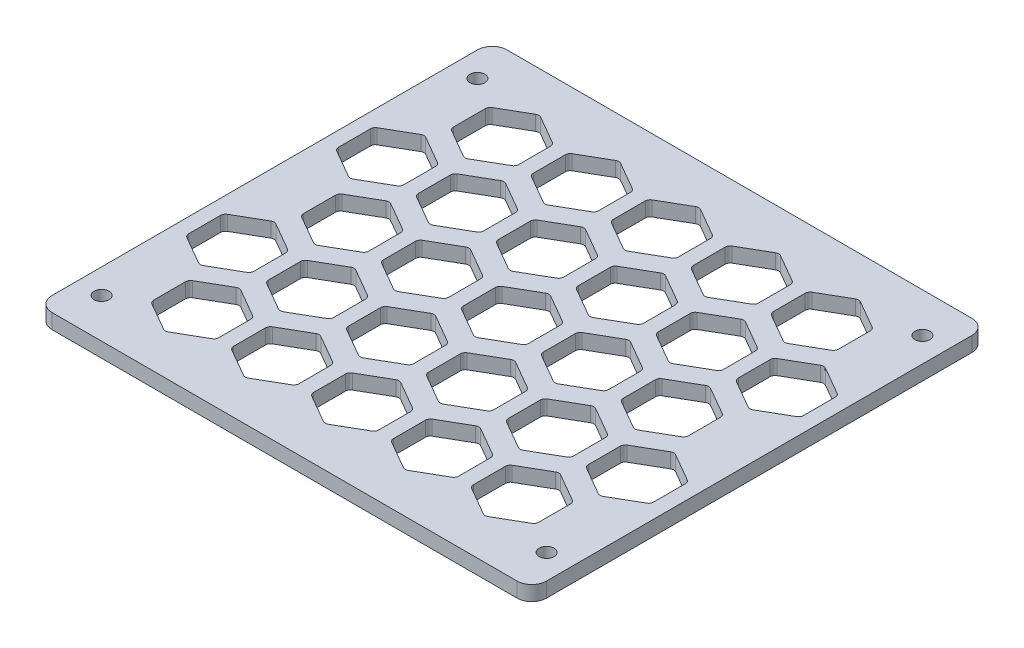
SolidWorks part; units mm, degrees
ref_plane "前视基准面" through (0, 0, 0) normal (0, 0, 1) x (1, 0, 0)
ref_plane "上视基准面" through (0, 0, 0) normal (0, 1, 0) x (1, 0, 0)
ref_plane "右视基准面" through (0, 0, 0) normal (1, 0, 0) x (0, 0, -1)
other "Configuration Table"
sketch "草图1" plane through (0, 0, 0) normal (0, 1, 0) x (1, 0, 0)
  line L1 (-50, 46) -> (50, 46)
  line L2 (-50, 46) -> (-50, -46)
  line L3 (-50, -46) -> (50, -46)
  line L4 (50, 46) -> (50, -46)
  line L5 (-50, 46) -> (50, -46) construction
  line L6 (-50, -46) -> (50, 46) construction
  line L7 (-45, -38) -> (45, -38) construction
  line L8 (-45, -38) -> (-45, 38) construction
  line L9 (-45, 38) -> (45, 38) construction
  line L10 (45, -38) -> (45, 38) construction
  line L11 (-45, -38) -> (45, 38) construction
  line L12 (-45, 38) -> (45, -38) construction
  circle A1 centre (-45, 38) radius 1.5
  circle A2 centre (45, 38) radius 1.5
  circle A3 centre (45, -38) radius 1.5
  circle A4 centre (-45, -38) radius 1.5
  point P0 (0, 0)
  point P6 (0, 0)
  dimension "D5" = 3
  dimension "D1" = 100
  dimension "D2" = 92
  dimension "D3" = 5
  dimension "D4" = 8
extrude "凸台-拉伸1" add sketch "草图1" along normal blind 3
fillet "圆角1" radius 3 4 edges at (-50, 1.5, 46) (-50, 1.5, -46) (50, 1.5, -46) (50, 1.5, 46)
sketch "草图2" plane through (0, 3, 0) normal (0, 1, 0) x (1, 0, 0)
  line L0 (0, 0) -> (0, 46) construction
  line L1 (-32.3333, 22.7091) -> (-25.75, 26.51)
  line L2 (-25.75, 26.51) -> (-25.75, 34.1118)
  line L3 (-25.75, 34.1118) -> (-32.3333, 37.9127)
  line L4 (-32.3333, 37.9127) -> (-38.9167, 34.1118)
  line L5 (-38.9167, 34.1118) -> (-38.9167, 26.51)
  line L6 (-38.9167, 26.51) -> (-32.3333, 22.7091)
  line L13 (-16.1667, 37.9127) -> (-22.75, 34.1118)
  line L14 (-22.75, 34.1118) -> (-22.75, 26.51)
  line L15 (-22.75, 26.51) -> (-16.1667, 22.7091)
  line L16 (-16.1667, 22.7091) -> (-9.5833, 26.51)
  line L17 (-9.5833, 26.51) -> (-9.5833, 34.1118)
  line L18 (-9.5833, 34.1118) -> (-16.1667, 37.9127)
  line L19 (47, 46) -> (-47, 46) construction
  line L20 (-32.3333, 30.3109) -> (0, 30.3109) construction
  line L21 (0, 37.9127) -> (-6.5833, 34.1118)
  line L22 (-6.5833, 34.1118) -> (-6.5833, 26.51)
  line L23 (-6.5833, 26.51) -> (0, 22.7091)
  line L24 (0, 22.7091) -> (6.5833, 26.51)
  line L25 (6.5833, 26.51) -> (6.5833, 34.1118)
  line L26 (6.5833, 34.1118) -> (0, 37.9127)
  line L27 (-40.4167, 15.1554) -> (-8.0833, 15.1554) construction
  line L28 (-40.4167, 22.7572) -> (-47, 18.9563)
  line L29 (-47, 18.9563) -> (-47, 11.3546)
  line L30 (-47, 11.3546) -> (-40.4167, 7.5537)
  line L31 (-40.4167, 7.5537) -> (-33.8333, 11.3546)
  line L32 (-33.8333, 11.3546) -> (-33.8333, 18.9563)
  line L33 (-33.8333, 18.9563) -> (-40.4167, 22.7572)
  line L34 (-24.25, 22.7572) -> (-30.8333, 18.9563)
  line L35 (-30.8333, 18.9563) -> (-30.8333, 11.3546)
  line L36 (-30.8333, 11.3546) -> (-24.25, 7.5537)
  line L37 (-24.25, 7.5537) -> (-17.6667, 11.3546)
  line L38 (-17.6667, 11.3546) -> (-17.6667, 18.9563)
  line L39 (-17.6667, 18.9563) -> (-24.25, 22.7572)
  line L40 (-8.0833, 22.7572) -> (-14.6667, 18.9563)
  line L41 (-14.6667, 18.9563) -> (-14.6667, 11.3546)
  line L42 (-14.6667, 11.3546) -> (-8.0833, 7.5537)
  line L43 (-8.0833, 7.5537) -> (-1.5, 11.3546)
  line L44 (-1.5, 11.3546) -> (-1.5, 18.9563)
  line L45 (-1.5, 18.9563) -> (-8.0833, 22.7572)
  line L46 (-32.3333, 0) -> (0, 0) construction
  line L47 (6.5833, -3.8009) -> (0, -7.6018)
  line L48 (6.5833, 3.8009) -> (6.5833, -3.8009)
  line L49 (0, 7.6018) -> (6.5833, 3.8009)
  line L50 (-6.5833, 3.8009) -> (0, 7.6018)
  line L51 (-6.5833, -3.8009) -> (-6.5833, 3.8009)
  line L52 (0, -7.6018) -> (-6.5833, -3.8009)
  line L53 (-9.5833, -3.8009) -> (-16.1667, -7.6018)
  line L54 (-9.5833, 3.8009) -> (-9.5833, -3.8009)
  line L55 (-16.1667, 7.6018) -> (-9.5833, 3.8009)
  line L56 (-22.75, 3.8009) -> (-16.1667, 7.6018)
  line L57 (-22.75, -3.8009) -> (-22.75, 3.8009)
  line L58 (-16.1667, -7.6018) -> (-22.75, -3.8009)
  line L59 (-38.9167, 3.8009) -> (-32.3333, 7.6018)
  line L60 (-38.9167, -3.8009) -> (-38.9167, 3.8009)
  line L61 (-32.3333, -7.6018) -> (-38.9167, -3.8009)
  line L62 (-25.75, -3.8009) -> (-32.3333, -7.6018)
  line L63 (-25.75, 3.8009) -> (-25.75, -3.8009)
  line L64 (-32.3333, 7.6018) -> (-25.75, 3.8009)
  line L66 (-50, 43) -> (-50, -43) construction
  line L67 (9.5833, 3.8009) -> (9.5833, -3.8009)
  line L68 (16.1667, 7.6018) -> (9.5833, 3.8009)
  line L69 (22.75, 3.8009) -> (16.1667, 7.6018)
  line L70 (22.75, -3.8009) -> (22.75, 3.8009)
  line L71 (16.1667, -7.6018) -> (22.75, -3.8009)
  line L72 (9.5833, -3.8009) -> (16.1667, -7.6018)
  line L73 (38.9167, -3.8009) -> (38.9167, 3.8009)
  line L74 (32.3333, -7.6018) -> (38.9167, -3.8009)
  line L75 (25.75, -3.8009) -> (32.3333, -7.6018)
  line L76 (25.75, 3.8009) -> (25.75, -3.8009)
  line L77 (32.3333, 7.6018) -> (25.75, 3.8009)
  line L78 (38.9167, 3.8009) -> (32.3333, 7.6018)
  line L79 (33.8333, 18.9563) -> (40.4167, 22.7572)
  line L80 (33.8333, 11.3546) -> (33.8333, 18.9563)
  line L81 (40.4167, 7.5537) -> (33.8333, 11.3546)
  line L82 (47, 11.3546) -> (40.4167, 7.5537)
  line L83 (47, 18.9563) -> (47, 11.3546)
  line L84 (40.4167, 22.7572) -> (47, 18.9563)
  line L85 (1.5, 18.9563) -> (8.0833, 22.7572)
  line L86 (1.5, 11.3546) -> (1.5, 18.9563)
  line L87 (8.0833, 7.5537) -> (1.5, 11.3546)
  line L88 (14.6667, 11.3546) -> (8.0833, 7.5537)
  line L89 (14.6667, 18.9563) -> (14.6667, 11.3546)
  line L90 (8.0833, 22.7572) -> (14.6667, 18.9563)
  line L91 (17.6667, 18.9563) -> (24.25, 22.7572)
  line L92 (17.6667, 11.3546) -> (17.6667, 18.9563)
  line L93 (24.25, 7.5537) -> (17.6667, 11.3546)
  line L94 (30.8333, 11.3546) -> (24.25, 7.5537)
  line L95 (30.8333, 18.9563) -> (30.8333, 11.3546)
  line L96 (24.25, 22.7572) -> (30.8333, 18.9563)
  line L97 (9.5833, 34.1118) -> (16.1667, 37.9127)
  line L98 (9.5833, 26.51) -> (9.5833, 34.1118)
  line L99 (16.1667, 22.7091) -> (9.5833, 26.51)
  line L100 (22.75, 26.51) -> (16.1667, 22.7091)
  line L101 (22.75, 34.1118) -> (22.75, 26.51)
  line L102 (16.1667, 37.9127) -> (22.75, 34.1118)
  line L103 (38.9167, 26.51) -> (32.3333, 22.7091)
  line L104 (38.9167, 34.1118) -> (38.9167, 26.51)
  line L105 (32.3333, 37.9127) -> (38.9167, 34.1118)
  line L106 (25.75, 34.1118) -> (32.3333, 37.9127)
  line L107 (25.75, 26.51) -> (25.75, 34.1118)
  line L108 (32.3333, 22.7091) -> (25.75, 26.51)
  line L109 (-40.4167, -15.1554) -> (-8.0833, -15.1554) construction
  line L110 (-32.3333, -30.3109) -> (0, -30.3109) construction
  line L111 (32.3333, -22.7091) -> (25.75, -26.51)
  line L112 (25.75, -26.51) -> (25.75, -34.1118)
  line L113 (25.75, -34.1118) -> (32.3333, -37.9127)
  line L114 (32.3333, -37.9127) -> (38.9167, -34.1118)
  line L115 (38.9167, -34.1118) -> (38.9167, -26.51)
  line L116 (38.9167, -26.51) -> (32.3333, -22.7091)
  line L117 (16.1667, -37.9127) -> (22.75, -34.1118)
  line L118 (22.75, -34.1118) -> (22.75, -26.51)
  line L119 (22.75, -26.51) -> (16.1667, -22.7091)
  line L120 (16.1667, -22.7091) -> (9.5833, -26.51)
  line L121 (9.5833, -26.51) -> (9.5833, -34.1118)
  line L122 (9.5833, -34.1118) -> (16.1667, -37.9127)
  line L123 (24.25, -22.7572) -> (30.8333, -18.9563)
  line L124 (30.8333, -18.9563) -> (30.8333, -11.3546)
  line L125 (30.8333, -11.3546) -> (24.25, -7.5537)
  line L126 (24.25, -7.5537) -> (17.6667, -11.3546)
  line L127 (17.6667, -11.3546) -> (17.6667, -18.9563)
  line L128 (17.6667, -18.9563) -> (24.25, -22.7572)
  line L129 (8.0833, -22.7572) -> (14.6667, -18.9563)
  line L130 (14.6667, -18.9563) -> (14.6667, -11.3546)
  line L131 (14.6667, -11.3546) -> (8.0833, -7.5537)
  line L132 (8.0833, -7.5537) -> (1.5, -11.3546)
  line L133 (1.5, -11.3546) -> (1.5, -18.9563)
  line L134 (1.5, -18.9563) -> (8.0833, -22.7572)
  line L135 (40.4167, -22.7572) -> (47, -18.9563)
  line L136 (47, -18.9563) -> (47, -11.3546)
  line L137 (47, -11.3546) -> (40.4167, -7.5537)
  line L138 (40.4167, -7.5537) -> (33.8333, -11.3546)
  line L139 (33.8333, -11.3546) -> (33.8333, -18.9563)
  line L140 (33.8333, -18.9563) -> (40.4167, -22.7572)
  line L141 (-1.5, -18.9563) -> (-8.0833, -22.7572)
  line L142 (-1.5, -11.3546) -> (-1.5, -18.9563)
  line L143 (-8.0833, -7.5537) -> (-1.5, -11.3546)
  line L144 (-14.6667, -11.3546) -> (-8.0833, -7.5537)
  line L145 (-14.6667, -18.9563) -> (-14.6667, -11.3546)
  line L146 (-8.0833, -22.7572) -> (-14.6667, -18.9563)
  line L147 (-17.6667, -18.9563) -> (-24.25, -22.7572)
  line L148 (-17.6667, -11.3546) -> (-17.6667, -18.9563)
  line L149 (-24.25, -7.5537) -> (-17.6667, -11.3546)
  line L150 (-30.8333, -11.3546) -> (-24.25, -7.5537)
  line L151 (-30.8333, -18.9563) -> (-30.8333, -11.3546)
  line L152 (-24.25, -22.7572) -> (-30.8333, -18.9563)
  line L153 (-33.8333, -18.9563) -> (-40.4167, -22.7572)
  line L154 (-33.8333, -11.3546) -> (-33.8333, -18.9563)
  line L155 (-40.4167, -7.5537) -> (-33.8333, -11.3546)
  line L156 (-47, -11.3546) -> (-40.4167, -7.5537)
  line L157 (-47, -18.9563) -> (-47, -11.3546)
  line L158 (-40.4167, -22.7572) -> (-47, -18.9563)
  line L159 (6.5833, -34.1118) -> (0, -37.9127)
  line L160 (6.5833, -26.51) -> (6.5833, -34.1118)
  line L161 (0, -22.7091) -> (6.5833, -26.51)
  line L162 (-6.5833, -26.51) -> (0, -22.7091)
  line L163 (-6.5833, -34.1118) -> (-6.5833, -26.51)
  line L164 (0, -37.9127) -> (-6.5833, -34.1118)
  line L165 (-9.5833, -34.1118) -> (-16.1667, -37.9127)
  line L166 (-9.5833, -26.51) -> (-9.5833, -34.1118)
  line L167 (-16.1667, -22.7091) -> (-9.5833, -26.51)
  line L168 (-22.75, -26.51) -> (-16.1667, -22.7091)
  line L169 (-22.75, -34.1118) -> (-22.75, -26.51)
  line L170 (-16.1667, -37.9127) -> (-22.75, -34.1118)
  line L171 (-38.9167, -26.51) -> (-32.3333, -22.7091)
  line L172 (-38.9167, -34.1118) -> (-38.9167, -26.51)
  line L173 (-32.3333, -37.9127) -> (-38.9167, -34.1118)
  line L174 (-25.75, -34.1118) -> (-32.3333, -37.9127)
  line L175 (-25.75, -26.51) -> (-25.75, -34.1118)
  line L176 (-32.3333, -22.7091) -> (-25.75, -26.51)
  circle A0 centre (-32.3333, 30.3109) radius 6.5833 construction
  circle A1 centre (-40.4167, 15.1554) radius 6.5833 construction
  circle A2 centre (-16.1667, 30.3109) radius 6.5833 construction
  circle A3 centre (0, 30.3109) radius 6.5833 construction
  circle A4 centre (-24.25, 15.1554) radius 6.5833 construction
  circle A5 centre (-8.0833, 15.1554) radius 6.5833 construction
  circle A6 centre (-8.0833, -15.1554) radius 6.5833 construction
  circle A7 centre (-24.25, -15.1554) radius 6.5833 construction
  circle A8 centre (0, -30.3109) radius 6.5833 construction
  circle A9 centre (-16.1667, -30.3109) radius 6.5833 construction
  circle A10 centre (-40.4167, -15.1554) radius 6.5833 construction
  circle A11 centre (-32.3333, -30.3109) radius 6.5833 construction
  point P54 (-31.7945, 37.9576)
  point P73 (0, -0.4778)
  point P74 (-16.2312, 27.9856)
  point P75 (-41.9673, 18.0215)
  point P76 (-35.2095, 34.8683)
  point P77 (-41.0711, 16.7008)
  point P78 (-24.8958, 16.5127)
  point P79 (-47.3719, 13.1271)
  point P82 (-46.5903, 17.3553)
  point P85 (-47.9709, 4.5795)
  dimension "D1" = 3
  dimension "D2" = 4
  dimension "D3" = 3
  dimension "D4" = 3
  dimension "D5" = 3
extrude "切除-拉伸1" cut sketch "草图2" against normal blind 10
fillet "圆角2" radius 1 119 edges at (-25.75, 1.5, -34.1118) (-25.75, 1.5, -26.51) (-38.9167, 1.5, -26.51) (-8.0833, 1.5, 22.7572) (-14.6667, 1.5, 18.9563) (-14.6667, 1.5, 11.3546) (-8.0833, 1.5, 7.5537) (-1.5, 1.5, 11.3546) (-1.5, 1.5, 18.9563) (-24.25, 1.5, 22.7572) (-30.8333, 1.5, 18.9563) (-30.8333, 1.5, 11.3546) (-24.25, 1.5, 7.5537) (-17.6667, 1.5, 11.3546) (-17.6667, 1.5, 18.9563) (-40.4167, 1.5, 22.7572) (-47, 1.5, 18.9563) (-47, 1.5, 11.3546) (-33.8333, 1.5, 11.3546) (0, 1.5, 37.9127) (-6.5833, 1.5, 34.1118) (-6.5833, 1.5, 26.51) (0, 1.5, 22.7091) (6.5833, 1.5, 26.51) (6.5833, 1.5, 34.1118) (24.25, 1.5, 7.5537) (30.8333, 1.5, 11.3546) (30.8333, 1.5, 18.9563) (24.25, 1.5, 22.7572) (17.6667, 1.5, 18.9563) (16.1667, 1.5, 22.7091) (22.75, 1.5, 26.51) (22.75, 1.5, 34.1118) (16.1667, 1.5, 37.9127) (9.5833, 1.5, 34.1118) (1.5, 1.5, 11.3546) (8.0833, 1.5, 22.7572) (1.5, 1.5, 18.9563) (33.8333, 1.5, 11.3546) (40.4167, 1.5, 7.5537) (47, 1.5, 11.3546) (47, 1.5, 18.9563) (40.4167, 1.5, 22.7572) (33.8333, 1.5, 18.9563) (-22.75, 1.5, 34.1118) (-22.75, 1.5, 26.51) (-16.1667, 1.5, 22.7091) (-9.5833, 1.5, 34.1118) (-32.3333, 1.5, 22.7091) (-25.75, 1.5, 26.51) (-32.3333, 1.5, 37.9127) (-38.9167, 1.5, 26.51) (0, 1.5, 7.6018) (-6.5833, 1.5, 3.8009) (0, 1.5, -7.6018) (6.5833, 1.5, -3.8009) (6.5833, 1.5, 3.8009) (-1.5, 1.5, -11.3546) (-8.0833, 1.5, -7.5537) (-8.0833, 1.5, -22.7572) (-1.5, 1.5, -18.9563) (-22.75, 1.5, 3.8009) (-22.75, 1.5, -3.8009) (-16.1667, 1.5, -7.6018) (-32.3333, 1.5, -7.6018) (-25.75, 1.5, -3.8009) (-32.3333, 1.5, 7.6018) (-38.9167, 1.5, 3.8009) (-38.9167, 1.5, -3.8009) (-17.6667, 1.5, -11.3546) (-30.8333, 1.5, -11.3546) (-30.8333, 1.5, -18.9563) (-24.25, 1.5, -22.7572) (-17.6667, 1.5, -18.9563) (-47, 1.5, -18.9563) (-40.4167, 1.5, -22.7572) (-9.5833, 1.5, -26.51) (-16.1667, 1.5, -22.7091) (-22.75, 1.5, -26.51) (-22.75, 1.5, -34.1118) (-16.1667, 1.5, -37.9127) (6.5833, 1.5, -26.51) (0, 1.5, -22.7091) (-6.5833, 1.5, -26.51) (-6.5833, 1.5, -34.1118) (0, 1.5, -37.9127) (6.5833, 1.5, -34.1118) (22.75, 1.5, -34.1118) (22.75, 1.5, -26.51) (9.5833, 1.5, -26.51) (9.5833, 1.5, -34.1118) (24.25, 1.5, -22.7572) (30.8333, 1.5, -18.9563) (30.8333, 1.5, -11.3546) (24.25, 1.5, -7.5537) (17.6667, 1.5, -18.9563) (32.3333, 1.5, -22.7091) (25.75, 1.5, -26.51) (25.75, 1.5, -34.1118) (32.3333, 1.5, -37.9127) (38.9167, 1.5, -34.1118) (38.9167, 1.5, -26.51) (38.9167, 1.5, 34.1118) (25.75, 1.5, 34.1118) (25.75, 1.5, 26.51) (22.75, 1.5, -3.8009) (16.1667, 1.5, 7.6018) (9.5833, 1.5, -3.8009) (25.75, 1.5, 3.8009) (32.3333, 1.5, -7.6018) (38.9167, 1.5, -3.8009) (32.3333, 1.5, 7.6018) (40.4167, 1.5, -22.7572) (47, 1.5, -11.3546) (33.8333, 1.5, -18.9563) (8.0833, 1.5, -22.7572) (14.6667, 1.5, -18.9563) (14.6667, 1.5, -11.3546) (8.0833, 1.5, -7.5537)
